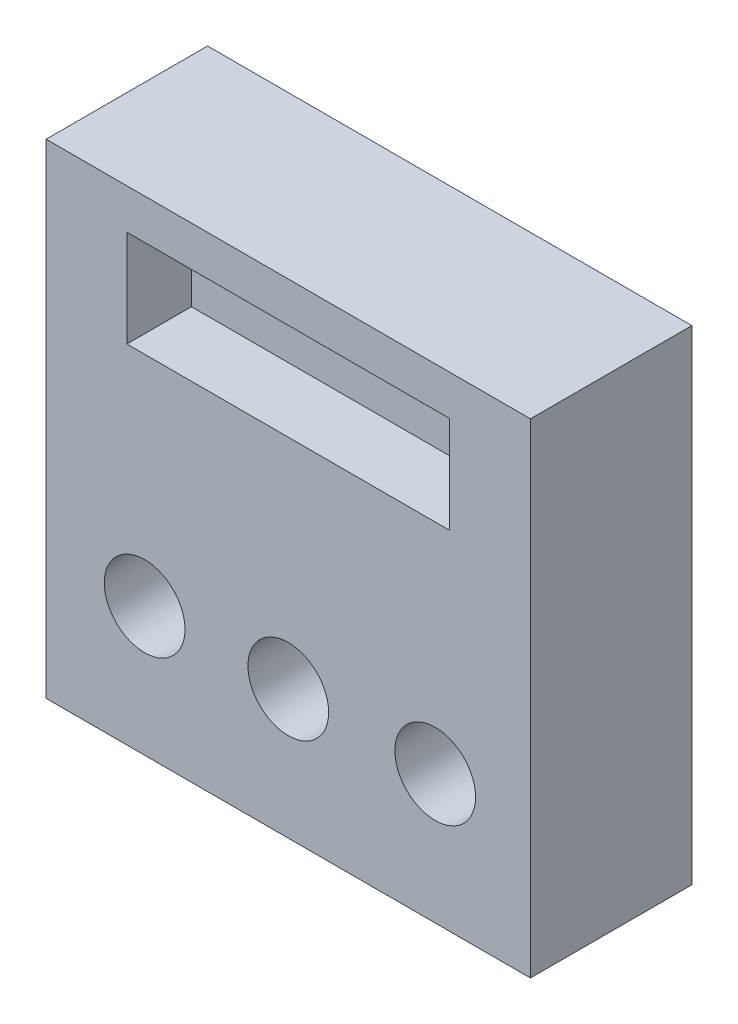
SolidWorks part; units mm, degrees
material "Plástico personalizado"
ref_plane "Plano frontal" through (0, 0, 0) normal (0, 0, 1) x (1, 0, 0)
ref_plane "Plano superior" through (0, 0, 0) normal (0, 1, 0) x (1, 0, 0)
ref_plane "Plano direito" through (0, 0, 0) normal (1, 0, 0) x (0, 0, -1)
sketch "Esboço1" plane through (0, 0, 0) normal (0, 0, 1) x (1, 0, 0)
  line L1 (-75, 75) -> (75, 75)
  line L2 (-75, 75) -> (-75, -75)
  line L3 (-75, -75) -> (75, -75)
  line L4 (75, 75) -> (75, -75)
  line L5 (-75, 75) -> (75, -75) construction
  line L6 (-75, -75) -> (75, 75) construction
  point P0 (0, 0)
  dimension "D1" = 150
  dimension "D2" = 150
extrude "Ressalto-extrusão1" add sketch "Esboço1" along normal blind 50
sketch "Esboço2" plane through (0, 0, 50) normal (0, 0, 1) x (1, 0, 0)
  line L0 (0, 75) -> (0, -75) construction
  line L1 (75, 75) -> (-75, 75) construction
  line L2 (-75, -75) -> (75, -75) construction
  line L4 (-50, 62.565) -> (50, 62.565)
  line L5 (-50, 62.565) -> (-50, 32.565)
  line L6 (-50, 32.565) -> (50, 32.565)
  line L7 (50, 62.565) -> (50, 32.565)
  line L8 (-50, 62.565) -> (50, 32.565) construction
  line L9 (-50, 32.565) -> (50, 62.565) construction
  point P6 (0, 47.565)
  dimension "D1" = 30
  dimension "D2" = 100
extrude "Corte-extrusão1" cut sketch "Esboço2" against normal blind 20
sketch "Esboço3" plane through (0, 0, 50) normal (0, 0, 1) x (1, 0, 0)
  line L0 (-75, -35) -> (75, -35) construction
  line L1 (-75, 75) -> (-75, -75) construction
  line L2 (75, -75) -> (75, 75) construction
  line L3 (-75, -75) -> (75, -75) construction
  circle A0 centre (-44.4939, -35) radius 12.5
  circle A1 centre (0, -35) radius 12.5
  circle A2 centre (45.5061, -35) radius 12.5
  dimension "D2" = 25
  dimension "D1" = 40
  dimension "D3" = 90
extrude "Corte-extrusão2" cut sketch "Esboço3" against normal blind 45
